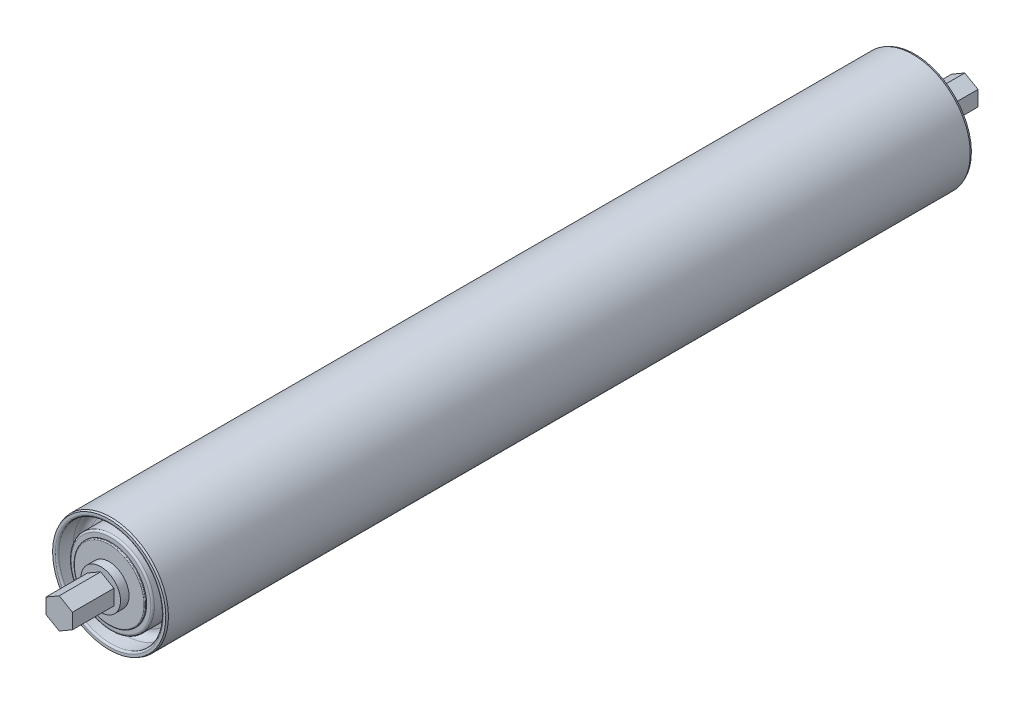
SolidWorks part; units mm, degrees
ref_plane "Front Plane" through (0, 0, 0) normal (0, 0, 1) x (1, 0, 0)
ref_plane "Top Plane" through (0, 0, 0) normal (0, 1, 0) x (1, 0, 0)
ref_plane "Right Plane" through (0, 0, 0) normal (1, 0, 0) x (0, 0, -1)
sketch "Sketch1" plane through (0, 0, 0) normal (1, 0, 0) x (0, 0, -1)
  line L0 (-190.5, 0) -> (190.5, 0) construction
  line L1 (-168.6719, 24.13) -> (168.6719, 24.13)
  line L2 (0, 24.13) -> (0, 0) construction
  line L3 (-190.5, 0) -> (-190.5, 5.5562)
  line L4 (-190.5, 5.5562) -> (-168.6719, 5.5562)
  line L5 (-174.625, 5.5562) -> (-174.625, -5.5562) construction
  line L6 (174.625, 5.5562) -> (174.625, -5.5562) construction
  line L7 (-174.625, -5.5562) -> (174.625, -5.5562) construction
  line L8 (-168.6719, 24.13) -> (-168.6719, 0) construction
  line L9 (-173.0375, 8.3344) -> (-173.0375, 0)
  line L10 (-173.0375, 8.3344) -> (-168.6719, 8.3344)
  line L11 (173.0375, 8.3344) -> (168.6719, 8.3344)
  line L12 (173.0375, 8.3344) -> (173.0375, 0)
  line L13 (190.5, 5.5563) -> (168.6719, 5.5563)
  line L14 (190.5, 0) -> (190.5, 5.5563)
  line L15 (-169.4656, 15.0019) -> (-168.7036, 15.0019) construction
  line L16 (-168.6719, 24.13) -> (-169.4656, 23.8125)
  line L17 (-169.4656, 23.8125) -> (-169.4656, 8.3344)
  line L18 (168.6719, 24.13) -> (169.4656, 23.8125)
  line L19 (169.4656, 23.8125) -> (169.4656, 8.3344)
  line L20 (-168.7036, 15.0019) -> (-168.7036, 17.5022) construction
  line L22 (-168.7036, 17.5022) -> (-159.5438, 17.5022) construction
  line L23 (-159.5438, 17.5022) -> (-159.5438, 21.971) construction
  line L24 (-159.5438, 21.971) -> (-169.4656, 21.971) construction
  arc A1 (-162.5918, 21.971) -> (-159.5437, 18.923) centre (-162.5918, 18.923) cw construction
  arc A2 (-169.4656, 22.733) -> (-168.7036, 21.971) centre (-168.7036, 22.733) ccw construction
  arc A3 (-168.7036, 16.7402) -> (-167.9416, 17.5022) centre (-167.9416, 16.7402) cw construction
  arc A4 (-169.4656, 14.6209) -> (-169.0846, 15.0019) centre (-169.0846, 14.6209) cw construction
  point P11 (-174.625, 0)
  point P12 (174.625, 0)
  point P13 (0, -5.5562)
  point P24 (-144.78, 0)
  point P27 (144.78, 0)
  point P32 (-159.5438, 19.7366)
  dimension "D14" = 3.048
  dimension "D15" = 0.762
  dimension "D16" = 0.381
  dimension "Overall Width" = 381
  dimension "Rollar Diameter" = 48.26
  dimension "Hex Axle Size" = 11.1125
  dimension "BF" = 349.25
  dimension "D2" = 16.6687
  dimension "D1" = 1.5875
  dimension "D5" = 15.875
  dimension "D6" = 45.72
  dimension "D7" = 45.72
  dimension "D3" = 4.3656
  dimension "D8" = 47.625
  dimension "D10" = 0.762
  dimension "D9" = 35.0044
  dimension "D11" = 30.0038
  dimension "D12" = 43.942
  dimension "D13" = 13.4937
  dimension "Rollar Width" = 338.9313
sketch "Sketch5" plane through (0, 0, 0) normal (0, 0, 1) x (1, 0, 0)
  circle A0 centre (0, 0) radius 24.13
  dimension "D1" = 48.26
sketch "Sketch3" plane through (0, 0, 0) normal (1, 0, 0) x (0, 0, -1)
  line L0 (190.5, 5.5563) -> (168.6719, 5.5563) construction
  line L1 (190.5, 0) -> (190.5, 5.5563) construction
  line L2 (-190.5, 0) -> (-190.5, 5.5562) construction
  line L3 (-190.5, 5.5562) -> (-168.6719, 5.5562) construction
  line L4 (169.4656, 23.8125) -> (169.4656, 8.3344) construction
  line L5 (168.6719, 24.13) -> (169.4656, 23.8125) construction
  line L6 (-168.6719, 24.13) -> (168.6719, 24.13) construction
  line L7 (-168.6719, 24.13) -> (-169.4656, 23.8125) construction
  line L8 (-169.4656, 23.8125) -> (-169.4656, 8.3344) construction
  line L9 (173.0375, 8.3344) -> (168.6719, 8.3344) construction
  line L10 (173.0375, 8.3344) -> (173.0375, 0) construction
  line L11 (-173.0375, 8.3344) -> (-173.0375, 0) construction
  line L12 (-173.0375, 8.3344) -> (-168.6719, 8.3344) construction
  line L13 (190.5, 5.5563) -> (173.0375, 5.5563)
  line L14 (190.5, 0) -> (190.5, 5.5563)
  line L15 (-190.5, 0) -> (-190.5, 5.5562)
  line L16 (-190.5, 5.5562) -> (-173.0375, 5.5562)
  line L17 (169.4656, 23.8125) -> (169.4656, 8.3344)
  line L18 (168.6719, 24.13) -> (169.4656, 23.8125)
  line L19 (-168.6719, 24.13) -> (168.6719, 24.13)
  line L20 (-168.6719, 24.13) -> (-169.4656, 23.8125)
  line L21 (-169.4656, 23.8125) -> (-169.4656, 8.3344)
  line L22 (173.0375, 8.3344) -> (169.4656, 8.3344)
  line L23 (173.0375, 8.3344) -> (173.0375, 5.5563)
  line L24 (-173.0375, 8.3344) -> (-173.0375, 5.5562)
  line L25 (-173.0375, 8.3344) -> (-169.4656, 8.3344)
  line L26 (-190.5, 0) -> (190.5, 0)
revolve "Revolve1" add sketch "Sketch3" angle 360 about L0
sketch "Sketch4" plane through (0, 0, 190.5) normal (0, 0, 1) x (1, 0, 0)
  line L1 (0, 6.4158) -> (-5.5562, 3.2079)
  line L2 (-5.5562, 3.2079) -> (-5.5562, -3.2079)
  line L3 (-5.5562, -3.2079) -> (0, -6.4158)
  line L4 (0, -6.4158) -> (5.5562, -3.2079)
  line L5 (5.5562, -3.2079) -> (5.5562, 3.2079)
  line L6 (5.5562, 3.2079) -> (0, 6.4158)
  circle A0 centre (0, 0) radius 5.5562 construction
extrude "Boss-Extrude1" add sketch "Sketch4" against normal up to surface (381 mm away) up to face at (0, -5.5562, -190.5)
sketch "Sketch6" plane through (0, 0, 0) normal (1, 0, 0) x (0, 0, -1)
  line L0 (-159.5438, 21.971) -> (-169.4656, 21.971) construction
  line L1 (-159.5438, 17.5022) -> (-159.5438, 21.971) construction
  line L2 (-168.7036, 17.5022) -> (-159.5438, 17.5022) construction
  line L3 (-168.7036, 15.0019) -> (-168.7036, 17.5022) construction
  line L4 (-169.4656, 15.0019) -> (-168.7036, 15.0019) construction
  line L5 (-162.5918, 21.971) -> (-168.7036, 21.971)
  line L6 (-159.5438, 17.5022) -> (-159.5437, 18.923)
  line L7 (-167.9416, 17.5022) -> (-159.5438, 17.5022)
  line L8 (-168.7036, 15.0019) -> (-168.7036, 16.7402)
  line L9 (-169.0846, 15.0019) -> (-168.7036, 15.0019)
  line L10 (-169.4656, 22.733) -> (-169.4656, 14.6209)
  arc A0 (-169.4656, 22.733) -> (-168.7036, 21.971) centre (-168.7036, 22.733) ccw construction
  arc A1 (-159.5437, 18.923) -> (-162.5918, 21.971) centre (-162.5918, 18.923) ccw construction
  arc A2 (-167.9416, 17.5022) -> (-168.7036, 16.7402) centre (-167.9416, 16.7402) ccw construction
  arc A3 (-169.0846, 15.0019) -> (-169.4656, 14.6209) centre (-169.0846, 14.6209) ccw construction
  arc A4 (-169.4656, 22.733) -> (-168.7036, 21.971) centre (-168.7036, 22.733) ccw
  arc A5 (-159.5437, 18.923) -> (-162.5918, 21.971) centre (-162.5918, 18.923) ccw
  arc A6 (-167.9416, 17.5022) -> (-168.7036, 16.7402) centre (-167.9416, 16.7402) ccw
  arc A7 (-169.0846, 15.0019) -> (-169.4656, 14.6209) centre (-169.0846, 14.6209) ccw
revolve "Cut-Revolve1" cut sketch "Sketch6" angle 360 about L0
mirror "Mirror2" about plane through (0, 0, 0) normal (0, 0, 1) of "Cut-Revolve1"
ref_plane "Contact Plane 1" through (0, 24.13, 0) normal (0, 1, 0) x (1, 0, 0)
equation "\"D2@Sketch1\"=\"Hex Axle Size@Sketch1\"*1.5"
equation "\"D7@Sketch1\"=\"D6@Sketch1\""
equation "\"D9@Sketch1\"=\"D2@Sketch1\"*2.1"
equation "\"D11@Sketch1\"=\"D2@Sketch1\"*1.8"
equation "\"D12@Sketch1\"=1.7+\"D10@Sketch1\""
equation "\"D16@Sketch1\"=\"D15@Sketch1\"/2"
